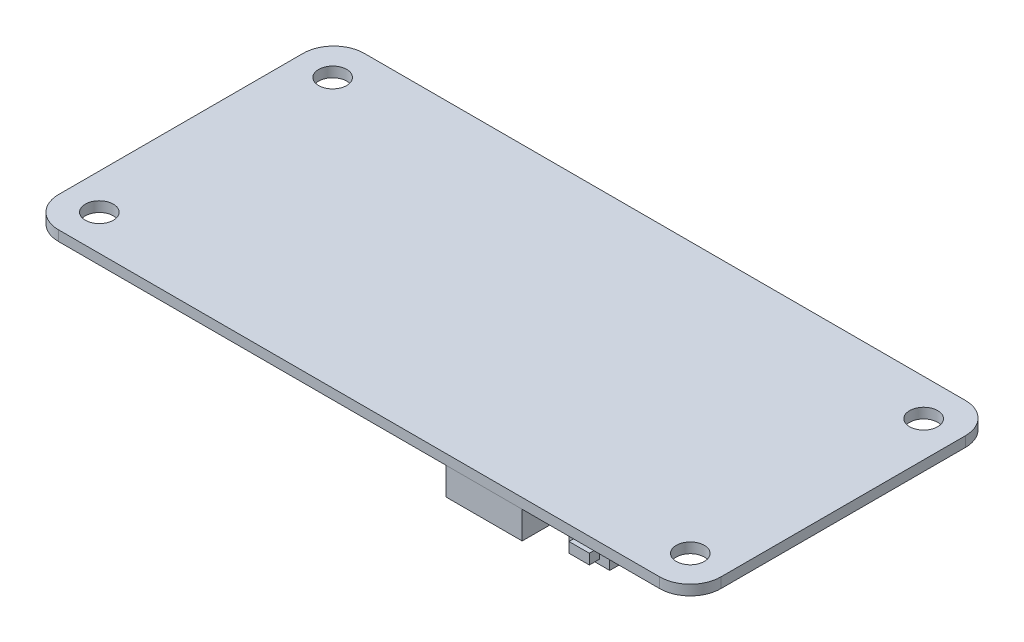
SolidWorks part; units mm, degrees
ref_plane "前视基准面" through (0, 0, 0) normal (0, 0, 1) x (1, 0, 0)
ref_plane "上视基准面" through (0, 0, 0) normal (0, 1, 0) x (1, 0, 0)
ref_plane "右视基准面" through (0, 0, 0) normal (1, 0, 0) x (0, 0, -1)
sketch "zero" plane through (0, 0, 0) normal (0, 1, 0) x (1, 0, 0)
  line L1 (-29.5, 15) -> (29.5, 15)
  line L2 (-32.5, 12) -> (-32.5, -12)
  line L3 (-29.5, -15) -> (29.5, -15)
  line L4 (32.5, 12) -> (32.5, -12)
  line L5 (-32.5, 15) -> (32.5, -15) construction
  line L6 (-32.5, -15) -> (32.5, 15) construction
  line L7 (-25.7, -15) -> (-14.5, -15)
  line L8 (-25.7, -15) -> (-25.7, -9.6569)
  line L9 (-25.7, -9.6569) -> (-14.5, -9.6569)
  line L10 (-14.5, -15) -> (-14.5, -9.6569)
  line L11 (5.2, -15) -> (12.7, -15)
  line L12 (5.2, -15) -> (5.2, -11)
  line L13 (5.2, -11) -> (12.7, -11)
  line L14 (12.7, -15) -> (12.7, -11)
  line L15 (17.8, -15) -> (25.3, -15)
  line L16 (17.8, -15) -> (17.8, -11)
  line L17 (17.8, -11) -> (25.3, -11)
  line L18 (25.3, -15) -> (25.3, -11)
  line L19 (-32.5, 7.7) -> (-19.5, 7.7)
  line L20 (-32.5, 7.7) -> (-32.5, -4.3)
  line L21 (-32.5, -4.3) -> (-19.5, -4.3)
  line L22 (-19.5, 7.7) -> (-19.5, -4.3)
  line L23 (-25.5, 14) -> (25.5, 14)
  line L24 (-25.5, 14) -> (-25.5, 8.8)
  line L25 (-25.5, 8.8) -> (25.5, 8.8)
  line L26 (25.5, 14) -> (25.5, 8.8)
  line L27 (-19.5, 7.2329) -> (-35.5, 7.2329)
  line L28 (-19.5, 7.2329) -> (-19.5, -3.7671)
  line L29 (-19.5, -3.7671) -> (-35.5, -3.7671)
  line L30 (-35.5, 7.2329) -> (-35.5, -3.7671)
  arc A0 (29.5, -15) -> (32.5, -12) centre (29.5, -12) ccw
  arc A1 (29.5, 15) -> (32.5, 12) centre (29.5, 12) cw
  arc A2 (-32.5, -12) -> (-29.5, -15) centre (-29.5, -12) ccw
  arc A3 (-29.5, 15) -> (-32.5, 12) centre (-29.5, 12) ccw
  circle A4 centre (-29, 11.4) radius 3
  circle A5 centre (-29, -11.5) radius 3
  circle A6 centre (29, 11.4) radius 3
  circle A7 centre (29, -11.5) radius 3
  circle A8 centre (-29, 11.4) radius 1.375
  circle A9 centre (-29, -11.5) radius 1.375
  circle A10 centre (29, -11.5) radius 1.375
  circle A11 centre (29, 11.4) radius 1.375
  point P0 (0, 0)
  dimension "D3" = 3
  dimension "D4" = 6
  dimension "D9" = 2.75
  dimension "D1" = 65
  dimension "D2" = 30
  dimension "D5" = 3.6
  dimension "D6" = 3.5
  dimension "D7" = 3.5
  dimension "D8" = 3.5
  dimension "D10" = 12
  dimension "D11" = 7.3
  dimension "D12" = 13
  dimension "D13" = 11.2
  dimension "D14" = 6.8
  dimension "D15" = 19.7
  dimension "D16" = 7.5
  dimension "D17" = 7.5
  dimension "D18" = 5.1
  dimension "D19" = 4
  dimension "D20" = 5.2
  dimension "D21" = 7
  dimension "D22" = 7
  dimension "D23" = 1
  dimension "D24" = 11
  dimension "D25" = 16
sketch "sugar" plane through (0, 0, 0) normal (0, 1, 0) x (1, 0, 0)
  line L1 (-29.5, 15) -> (29.5, 15)
  line L2 (-32.5, 12) -> (-32.5, -12)
  line L3 (-29.5, -15) -> (29.5, -15)
  line L4 (32.5, 12) -> (32.5, -12)
  line L5 (-32.5, 15) -> (32.5, -15) construction
  line L6 (-32.5, -15) -> (32.5, 15) construction
  line L7 (23.5, -11.5) -> (19.5, -11.5)
  line L8 (23.5, -11.5) -> (23.5, -13.9082)
  line L9 (23.5, -13.9082) -> (19.5, -13.9082)
  line L10 (19.5, -11.5) -> (19.5, -13.9082)
  line L11 (16, -11.0071) -> (8.5, -11.0071)
  line L12 (16, -11.0071) -> (16, -15)
  line L13 (16, -15) -> (8.5, -15)
  line L14 (8.5, -11.0071) -> (8.5, -15)
  line L15 (20.5, -13.9082) -> (22.5, -13.9082)
  line L16 (20.5, -13.9082) -> (20.5, -14.8173)
  line L17 (20.5, -14.8173) -> (22.5, -14.8173)
  line L18 (22.5, -13.9082) -> (22.5, -14.8173)
  arc A0 (29.5, 15) -> (32.5, 12) centre (29.5, 12) cw
  arc A1 (29.5, -15) -> (32.5, -12) centre (29.5, -12) ccw
  arc A2 (-32.5, -12) -> (-29.5, -15) centre (-29.5, -12) ccw
  arc A3 (-29.5, 15) -> (-32.5, 12) centre (-29.5, 12) ccw
  circle A4 centre (-29, 11.4) radius 3
  circle A5 centre (-29, 11.4) radius 1.375
  circle A6 centre (-29, -11.5) radius 3
  circle A7 centre (-29, -11.5) radius 1.375
  circle A8 centre (29, 11.4) radius 3
  circle A9 centre (29, 11.4) radius 1.375
  circle A10 centre (29, -11.5) radius 3
  circle A11 centre (29, -11.5) radius 1.375
  dimension "D3" = 3
  dimension "D1" = 65
  dimension "D2" = 30
  dimension "D4" = 9
  dimension "D5" = 4
  dimension "D6" = 3.5
  dimension "D7" = 7.5
  dimension "D8" = 2
  dimension "D9" = 1
sketch "草图1" plane through (0, 0, 0) normal (0, 1, 0) x (1, 0, 0)
  line L4 (-32.5, 12) -> (-32.5, -12)
  line L5 (-29.5, -15) -> (29.5, -15)
  line L6 (32.5, -12) -> (32.5, 12)
  line L7 (29.5, 15) -> (-29.5, 15)
  line L8 (-32.5, 12) -> (-32.5, -12)
  line L9 (-29.5, -15) -> (29.5, -15)
  line L10 (32.5, -12) -> (32.5, 12)
  line L11 (29.5, 15) -> (-29.5, 15)
  circle A1 centre (29, 11.4) radius 1.375
  circle A2 centre (29, 11.4) radius 1.375
  circle A3 centre (29, -11.5) radius 1.375
  circle A4 centre (29, -11.5) radius 1.375
  circle A5 centre (-29, -11.5) radius 1.375
  circle A6 centre (-29, -11.5) radius 1.375
  circle A7 centre (-29, 11.4) radius 1.375
  circle A8 centre (-29, 11.4) radius 1.375
  arc A20 (-32.5, -12) -> (-29.5, -15) centre (-29.5, -12) ccw
  arc A21 (29.5, -15) -> (32.5, -12) centre (29.5, -12) ccw
  arc A22 (32.5, 12) -> (29.5, 15) centre (29.5, 12) ccw
  arc A23 (-29.5, 15) -> (-32.5, 12) centre (-29.5, 12) ccw
  arc A24 (-32.5, -12) -> (-29.5, -15) centre (-29.5, -12) ccw
  arc A25 (29.5, -15) -> (32.5, -12) centre (29.5, -12) ccw
  arc A26 (32.5, 12) -> (29.5, 15) centre (29.5, 12) ccw
  arc A27 (-29.5, 15) -> (-32.5, 12) centre (-29.5, 12) ccw
  dimension "D1" = 0
  dimension "D2" = 0
  dimension "D3" = 0
  dimension "D4" = 0
  dimension "D9" = 0
extrude "凸台-拉伸2" add sketch "草图1" along normal blind 1
sketch "草图3" plane through (0, 0, 0) normal (0, 1, 0) x (1, 0, 0)
  line L20 (16, -11.0071) -> (8.5, -11.0071)
  line L21 (8.5, -11.0071) -> (8.5, -15)
  line L22 (8.5, -15) -> (16, -15)
  line L23 (16, -15) -> (16, -11.0071)
  line L24 (16, -11.0071) -> (8.5, -11.0071)
  line L25 (8.5, -11.0071) -> (8.5, -15)
  line L26 (8.5, -15) -> (16, -15)
  line L27 (16, -15) -> (16, -11.0071)
  dimension "D11" = 0
extrude "凸台-拉伸3" add sketch "草图3" against normal blind 2.7 separate body
sketch "草图4" plane through (0, 0, 0) normal (0, 1, 0) x (1, 0, 0)
  line L28 (23.5, -11.5) -> (19.5, -11.5)
  line L29 (19.5, -11.5) -> (19.5, -13.9082)
  line L30 (19.5, -13.9082) -> (23.5, -13.9082)
  line L31 (23.5, -13.9082) -> (23.5, -11.5)
  line L32 (23.5, -11.5) -> (19.5, -11.5)
  line L33 (19.5, -11.5) -> (19.5, -13.9082)
  line L34 (19.5, -13.9082) -> (23.5, -13.9082)
  line L35 (23.5, -13.9082) -> (23.5, -11.5)
  point P0 (0, 0)
  dimension "D12" = 0
extrude "凸台-拉伸4" add sketch "草图4" against normal blind 2 separate body
ref_plane "基准面1" through (0, 0, 13.9082) normal (0, 0, 1) x (1, 0, 0)
sketch "草图5" plane through (0, 0, 13.9082) normal (0, 0, 1) x (1, 0, 0)
  line L0 (23.5, -2) -> (23.5, 0) construction
  line L1 (20.5, -0.5358) -> (22.5, -0.5358)
  line L2 (20.5, -0.5358) -> (20.5, -1.5358)
  line L3 (20.5, -1.5358) -> (22.5, -1.5358)
  line L4 (22.5, -0.5358) -> (22.5, -1.5358)
  dimension "D1" = 2
  dimension "D2" = 1
  dimension "D3" = 1
extrude "凸台-拉伸5" add sketch "草图5" along normal blind 1
